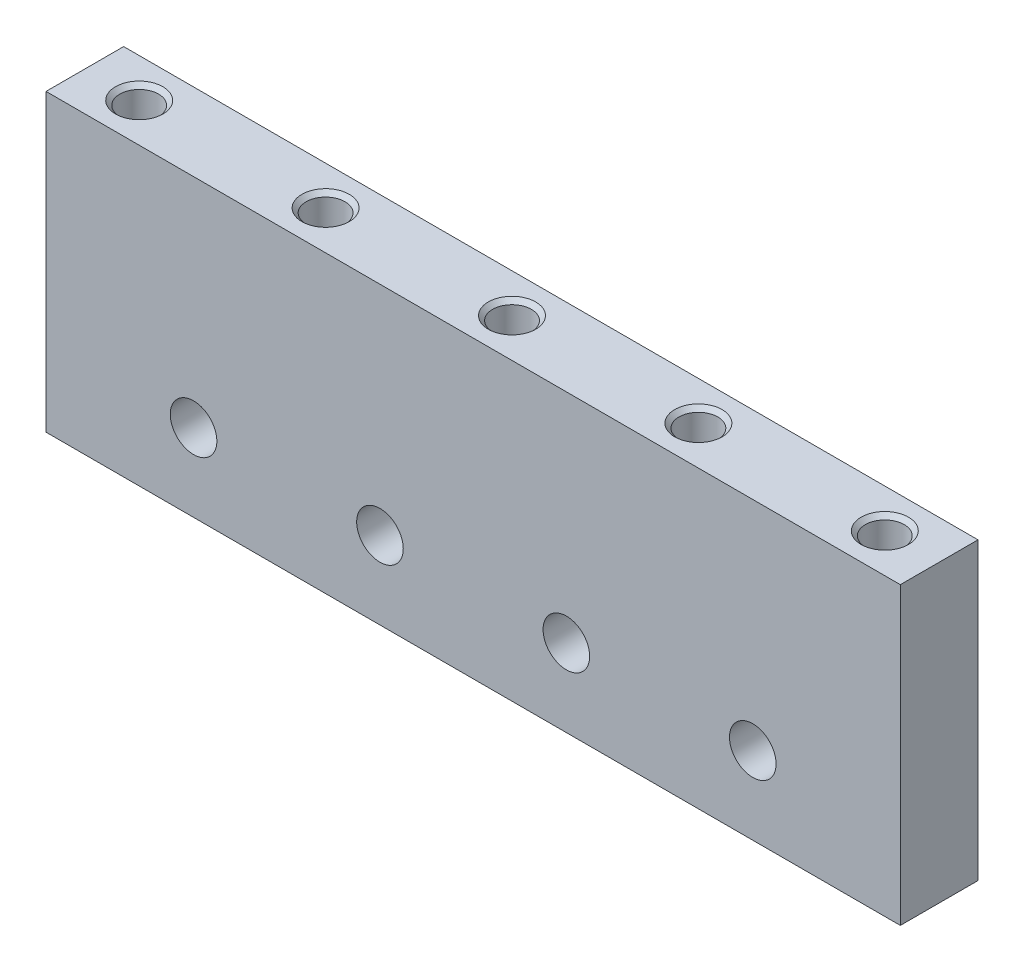
SolidWorks part; units mm, degrees
ref_plane "前基準面" through (0, 0, 0) normal (0, 0, 1) x (1, 0, 0)
ref_plane "上基準面" through (0, 0, 0) normal (0, 1, 0) x (1, 0, 0)
ref_plane "右基準面" through (0, 0, 0) normal (1, 0, 0) x (0, 0, -1)
sketch "草圖1" plane through (0, 0, 0) normal (0, 0, 1) x (1, 0, 0)
  line L0 (27.5, -4.5) -> (-27.5, -4.5) construction
  line L1 (-27.5, 9.5) -> (27.5, 9.5)
  line L2 (-27.5, 9.5) -> (-27.5, -9.5)
  line L3 (-27.5, -9.5) -> (27.5, -9.5)
  line L4 (27.5, 9.5) -> (27.5, -9.5)
  line L5 (-27.5, 9.5) -> (27.5, -9.5) construction
  line L6 (-27.5, -9.5) -> (27.5, 9.5) construction
  line L7 (0, -9.5) -> (0, 9.5) construction
  circle A0 centre (18, -4.5) radius 1.5
  circle A1 centre (6, -4.5) radius 1.5
  circle A2 centre (-6, -4.5) radius 1.5
  circle A3 centre (-18, -4.5) radius 1.5
  point P0 (0, 0)
  dimension "D5" = 3
  dimension "D1" = 55
  dimension "D2" = 19
  dimension "D3" = 14
  dimension "D4" = 18
  dimension "D7" = 12
  dimension "D6" = 4
extrude "填料-伸長1" add sketch "草圖1" along normal blind 5
sketch "草圖2" plane through (0, 9.5, 0) normal (0, 1, 0) x (1, 0, 0)
  line L0 (-27.5, -2.5) -> (27.5, -2.5) construction
  line L1 (-27.5, -5) -> (-27.5, 0) construction
  line L2 (27.5, -5) -> (27.5, 0) construction
  circle A0 centre (0, -2.5) radius 1.25
  circle A1 centre (-12, -2.5) radius 1.25
  circle A2 centre (12, -2.5) radius 1.25
  circle A3 centre (24, -2.5) radius 1.25
  circle A4 centre (0, -2.5) radius 1.25
  circle A5 centre (-24, -2.5) radius 1.25
  dimension "D1" = 2.5
  dimension "D4" = 2.5
  dimension "D5" = 2.5
  dimension "D2" = 12
  dimension "D3" = 12
  dimension "D6" = 2
  dimension "D7" = 2
hole_wizard "M3 螺紋孔2" positions "3D草圖2" profile "草圖4" tap size "M3" standard "ISO"
sketch3d "3D草圖2"
  point P0 (-24, 9.5, 2.5)
  point P3 (-12, 9.5, 2.5)
  point P6 (0, 9.5, 2.5)
  point P9 (12, 9.5, 2.5)
  point P12 (24, 9.5, 2.5)
sketch "草圖4" plane through (-24, 9.5, 2.5) normal (1, 0, 0) x (0, 0, 1)
  line L0 (0, 0) -> (0, 10.7511)
  line L1 (0, 10.7511) -> (1.25, 10)
  line L2 (1.25, 10) -> (1.25, 0.275)
  line L3 (1.25, 0.275) -> (1.525, 0)
  line L5 (1.525, 0) -> (0, 0)
  line L6 (-1.25, 0.275) -> (-1.525, 0) construction
  line L10 (0, 10.7511) -> (-1.25, 10) construction
  line L11 (0, -6.35) -> (0, 107.95) construction
  dimension "螺孔鑽直徑" = 2.5
  dimension "螺孔鑽深度" = 10
  dimension "近端錐孔直徑" = 3.05
  dimension "近端錐孔角度" = 90
  dimension "導頭角度" = 118
